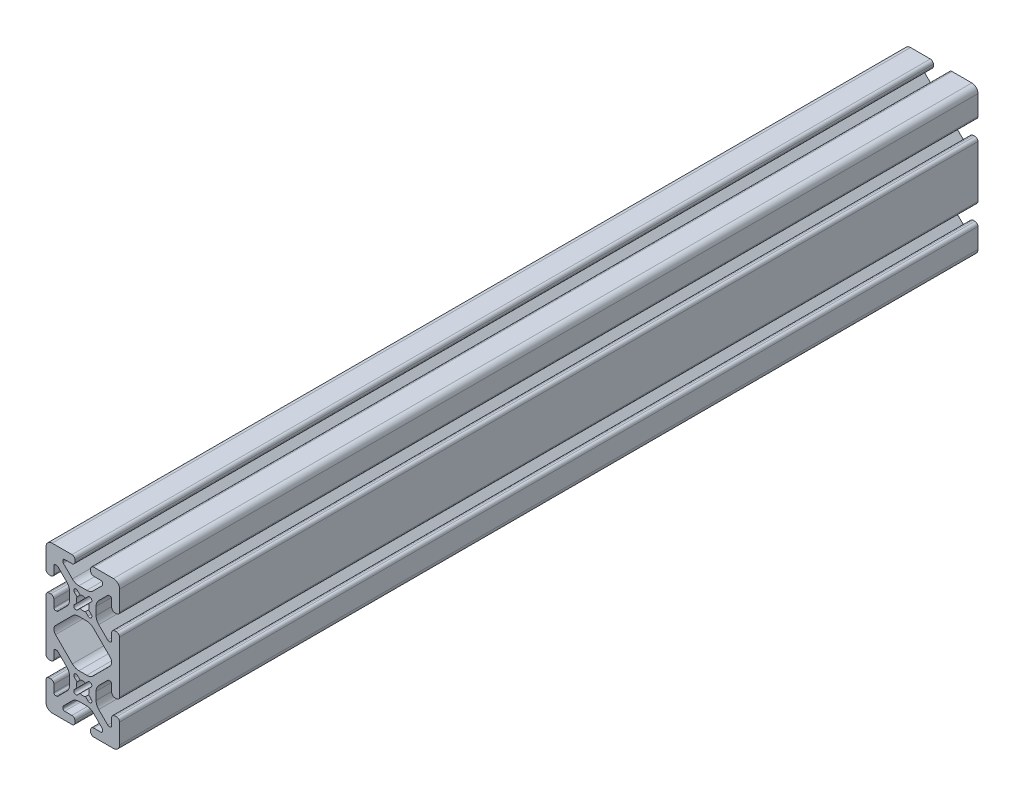
SolidWorks part; units mm, degrees
material "6063-T6"
ref_plane "Front Plane" through (0, 0, 0) normal (0, 0, 1) x (1, 0, 0)
ref_plane "Top Plane" through (0, 0, 0) normal (0, 1, 0) x (1, 0, 0)
ref_plane "Right Plane" through (0, 0, 0) normal (1, 0, 0) x (0, 0, -1)
ref_plane "Plane1" through (0, 0, -25.4) normal (0, 0, -1) x (-1, 0, 0)
sketch "Sketch1" plane through (0, 0, -25.4) normal (0, 0, -1) x (-1, 0, 0)
  line L0 (5.3872, 29.8392) -> (14.1109, 21.1155)
  line L1 (14.1109, 16.9845) -> (5.3872, 8.2608)
  line L2 (2.0285, 6.8697) -> (-2.0285, 6.8697)
  line L3 (-5.3872, 8.2608) -> (-14.1109, 16.9845)
  line L4 (-14.1109, 21.1155) -> (-5.3872, 29.8392)
  line L5 (-2.0285, 31.2303) -> (2.0285, 31.2303)
  line L6 (1.4014, 3.0179) -> (2.7269, 4.3433)
  line L7 (4.3433, 2.7269) -> (3.0179, 1.4014)
  line L8 (3.0179, -1.4014) -> (4.3433, -2.7269)
  line L9 (2.7269, -4.3433) -> (1.4014, -3.0179)
  line L10 (-1.4014, -3.0179) -> (-2.7269, -4.3433)
  line L11 (-4.3433, -2.7269) -> (-3.0179, -1.4014)
  line L12 (-3.0179, 1.4014) -> (-4.3433, 2.7269)
  line L13 (-2.7269, 4.3433) -> (-1.4014, 3.0179)
  line L14 (3.0179, 36.6986) -> (4.3433, 35.3731)
  line L15 (2.7269, 33.7567) -> (1.4014, 35.0821)
  line L16 (-1.4014, 35.0821) -> (-2.7269, 33.7567)
  line L17 (-4.3433, 35.3731) -> (-3.0179, 36.6986)
  line L18 (-3.0179, 39.5014) -> (-4.3433, 40.8269)
  line L19 (-2.7269, 42.4433) -> (-1.4014, 41.1179)
  line L20 (1.4014, 41.1179) -> (2.7269, 42.4433)
  line L21 (4.3433, 40.8269) -> (3.0179, 39.5014)
  line L22 (17.4752, 34.036) -> (16.5608, 34.036)
  line L23 (14.986, 32.4612) -> (14.986, 28.702)
  line L24 (14.097, 27.813) -> (13.5289, 27.813)
  line L25 (12.9003, 28.0734) -> (8.2608, 32.7128)
  line L26 (6.8697, 36.0715) -> (6.8697, 40.1285)
  line L27 (8.2608, 43.4872) -> (12.9003, 48.1266)
  line L28 (13.5289, 48.387) -> (14.097, 48.387)
  line L29 (14.986, 47.498) -> (14.986, 43.7388)
  line L30 (16.5608, 42.164) -> (17.4752, 42.164)
  line L31 (19.05, 43.7388) -> (19.05, 53.975)
  line L32 (15.875, 57.15) -> (5.6388, 57.15)
  line L33 (4.064, 55.5752) -> (4.064, 54.6608)
  line L34 (5.6388, 53.086) -> (9.398, 53.086)
  line L35 (10.287, 52.197) -> (10.287, 51.6289)
  line L36 (10.0266, 51.0003) -> (5.3872, 46.3608)
  line L37 (2.0285, 44.9697) -> (-2.0285, 44.9697)
  line L38 (-5.3872, 46.3608) -> (-10.0266, 51.0003)
  line L39 (-10.287, 51.6289) -> (-10.287, 52.197)
  line L40 (-9.398, 53.086) -> (-5.6388, 53.086)
  line L41 (-4.064, 54.6608) -> (-4.064, 55.5752)
  line L42 (-5.6388, 57.15) -> (-15.875, 57.15)
  line L43 (-19.05, 53.975) -> (-19.05, 43.7388)
  line L44 (-17.4752, 42.164) -> (-16.5608, 42.164)
  line L45 (-14.986, 43.7388) -> (-14.986, 47.498)
  line L46 (-14.097, 48.387) -> (-13.5289, 48.387)
  line L47 (-12.9003, 48.1266) -> (-8.2608, 43.4872)
  line L48 (-6.8697, 40.1285) -> (-6.8697, 36.0715)
  line L49 (-8.2608, 32.7128) -> (-12.9003, 28.0734)
  line L50 (-13.5289, 27.813) -> (-14.097, 27.813)
  line L51 (-14.986, 28.702) -> (-14.986, 32.4612)
  line L52 (-16.5608, 34.036) -> (-17.4752, 34.036)
  line L53 (-19.05, 32.4612) -> (-19.05, 5.6388)
  line L54 (-17.4752, 4.064) -> (-16.5608, 4.064)
  line L55 (-14.986, 5.6388) -> (-14.986, 9.398)
  line L56 (-14.097, 10.287) -> (-13.5289, 10.287)
  line L57 (-12.9003, 10.0266) -> (-8.2608, 5.3872)
  line L58 (-6.8697, 2.0285) -> (-6.8697, -2.0285)
  line L59 (-8.2608, -5.3872) -> (-12.9003, -10.0266)
  line L60 (-13.5289, -10.287) -> (-14.097, -10.287)
  line L61 (-14.986, -9.398) -> (-14.986, -5.6388)
  line L62 (-16.5608, -4.064) -> (-17.4752, -4.064)
  line L63 (-19.05, -5.6388) -> (-19.05, -15.875)
  line L64 (-15.875, -19.05) -> (-5.6388, -19.05)
  line L65 (-4.064, -17.4752) -> (-4.064, -16.5608)
  line L66 (-5.6388, -14.986) -> (-9.398, -14.986)
  line L67 (-10.287, -14.097) -> (-10.287, -13.5289)
  line L68 (-10.0266, -12.9003) -> (-5.3872, -8.2608)
  line L69 (-2.0285, -6.8697) -> (2.0285, -6.8697)
  line L70 (5.3872, -8.2608) -> (10.0266, -12.9003)
  line L71 (10.287, -13.5289) -> (10.287, -14.097)
  line L72 (9.398, -14.986) -> (5.6388, -14.986)
  line L73 (4.064, -16.5608) -> (4.064, -17.4752)
  line L74 (5.6388, -19.05) -> (15.875, -19.05)
  line L75 (19.05, -15.875) -> (19.05, -5.6388)
  line L76 (17.4752, -4.064) -> (16.5608, -4.064)
  line L77 (14.986, -5.6388) -> (14.986, -9.398)
  line L78 (14.097, -10.287) -> (13.5289, -10.287)
  line L79 (12.9003, -10.0266) -> (8.2608, -5.3872)
  line L80 (6.8697, -2.0285) -> (6.8697, 2.0285)
  line L81 (8.2608, 5.3872) -> (12.9003, 10.0266)
  line L82 (13.5289, 10.287) -> (14.097, 10.287)
  line L83 (14.986, 9.398) -> (14.986, 5.6388)
  line L84 (16.5608, 4.064) -> (17.4752, 4.064)
  line L85 (19.05, 5.6388) -> (19.05, 32.4612)
  arc A0 (14.1109, 21.1155) -> (14.1109, 16.9845) centre (12.0454, 19.05) cw
  arc A1 (5.3872, 8.2608) -> (2.0285, 6.8697) centre (2.0285, 11.6195) cw
  arc A2 (-2.0285, 6.8697) -> (-5.3872, 8.2608) centre (-2.0285, 11.6195) cw
  arc A3 (-14.1109, 16.9845) -> (-14.1109, 21.1155) centre (-12.0454, 19.05) cw
  arc A4 (-5.3872, 29.8392) -> (-2.0285, 31.2303) centre (-2.0285, 26.4805) cw
  arc A5 (2.0285, 31.2303) -> (5.3872, 29.8392) centre (2.0285, 26.4805) cw
  arc A6 (2.7269, 4.3433) -> (4.3433, 2.7269) centre (3.5351, 3.5351) cw
  arc A7 (3.0179, 1.4014) -> (3.0179, -1.4014) centre (0, 0) cw
  arc A8 (4.3433, -2.7269) -> (2.7269, -4.3433) centre (3.5351, -3.5351) cw
  arc A9 (1.4014, -3.0179) -> (-1.4014, -3.0179) centre (0, 0) cw
  arc A10 (-2.7269, -4.3433) -> (-4.3433, -2.7269) centre (-3.5351, -3.5351) cw
  arc A11 (-3.0179, -1.4014) -> (-3.0179, 1.4014) centre (0, 0) cw
  arc A12 (-4.3433, 2.7269) -> (-2.7269, 4.3433) centre (-3.5351, 3.5351) cw
  arc A13 (-1.4014, 3.0179) -> (1.4014, 3.0179) centre (0, 0) cw
  arc A14 (4.3433, 35.3731) -> (2.7269, 33.7567) centre (3.5351, 34.5649) cw
  arc A15 (1.4014, 35.0821) -> (-1.4014, 35.0821) centre (0, 38.1) cw
  arc A16 (-2.7269, 33.7567) -> (-4.3433, 35.3731) centre (-3.5351, 34.5649) cw
  arc A17 (-3.0179, 36.6986) -> (-3.0179, 39.5014) centre (0, 38.1) cw
  arc A18 (-4.3433, 40.8269) -> (-2.7269, 42.4433) centre (-3.5351, 41.6351) cw
  arc A19 (-1.4014, 41.1179) -> (1.4014, 41.1179) centre (0, 38.1) cw
  arc A20 (2.7269, 42.4433) -> (4.3433, 40.8269) centre (3.5351, 41.6351) cw
  arc A21 (3.0179, 39.5014) -> (3.0179, 36.6986) centre (0, 38.1) cw
  arc A22 (19.05, 32.4612) -> (17.4752, 34.036) centre (17.4752, 32.4612) ccw
  arc A23 (16.5608, 34.036) -> (14.986, 32.4612) centre (16.5608, 32.4612) ccw
  arc A24 (14.986, 28.702) -> (14.097, 27.813) centre (14.097, 28.702) cw
  arc A25 (13.5289, 27.813) -> (12.9003, 28.0734) centre (13.5289, 28.702) cw
  arc A26 (8.2608, 32.7128) -> (6.8697, 36.0715) centre (11.6195, 36.0715) cw
  arc A27 (6.8697, 40.1285) -> (8.2608, 43.4872) centre (11.6195, 40.1285) cw
  arc A28 (12.9003, 48.1266) -> (13.5289, 48.387) centre (13.5289, 47.498) cw
  arc A29 (14.097, 48.387) -> (14.986, 47.498) centre (14.097, 47.498) cw
  arc A30 (14.986, 43.7388) -> (16.5608, 42.164) centre (16.5608, 43.7388) ccw
  arc A31 (17.4752, 42.164) -> (19.05, 43.7388) centre (17.4752, 43.7388) ccw
  arc A32 (19.05, 53.975) -> (15.875, 57.15) centre (15.875, 53.975) ccw
  arc A33 (5.6388, 57.15) -> (4.064, 55.5752) centre (5.6388, 55.5752) ccw
  arc A34 (4.064, 54.6608) -> (5.6388, 53.086) centre (5.6388, 54.6608) ccw
  arc A35 (9.398, 53.086) -> (10.287, 52.197) centre (9.398, 52.197) cw
  arc A36 (10.287, 51.6289) -> (10.0266, 51.0003) centre (9.398, 51.6289) cw
  arc A37 (5.3872, 46.3608) -> (2.0285, 44.9697) centre (2.0285, 49.7195) cw
  arc A38 (-2.0285, 44.9697) -> (-5.3872, 46.3608) centre (-2.0285, 49.7195) cw
  arc A39 (-10.0266, 51.0003) -> (-10.287, 51.6289) centre (-9.398, 51.6289) cw
  arc A40 (-10.287, 52.197) -> (-9.398, 53.086) centre (-9.398, 52.197) cw
  arc A41 (-5.6388, 53.086) -> (-4.064, 54.6608) centre (-5.6388, 54.6608) ccw
  arc A42 (-4.064, 55.5752) -> (-5.6388, 57.15) centre (-5.6388, 55.5752) ccw
  arc A43 (-15.875, 57.15) -> (-19.05, 53.975) centre (-15.875, 53.975) ccw
  arc A44 (-19.05, 43.7388) -> (-17.4752, 42.164) centre (-17.4752, 43.7388) ccw
  arc A45 (-16.5608, 42.164) -> (-14.986, 43.7388) centre (-16.5608, 43.7388) ccw
  arc A46 (-14.986, 47.498) -> (-14.097, 48.387) centre (-14.097, 47.498) cw
  arc A47 (-13.5289, 48.387) -> (-12.9003, 48.1266) centre (-13.5289, 47.498) cw
  arc A48 (-8.2608, 43.4872) -> (-6.8697, 40.1285) centre (-11.6195, 40.1285) cw
  arc A49 (-6.8697, 36.0715) -> (-8.2608, 32.7128) centre (-11.6195, 36.0715) cw
  arc A50 (-12.9003, 28.0734) -> (-13.5289, 27.813) centre (-13.5289, 28.702) cw
  arc A51 (-14.097, 27.813) -> (-14.986, 28.702) centre (-14.097, 28.702) cw
  arc A52 (-14.986, 32.4612) -> (-16.5608, 34.036) centre (-16.5608, 32.4612) ccw
  arc A53 (-17.4752, 34.036) -> (-19.05, 32.4612) centre (-17.4752, 32.4612) ccw
  arc A54 (-19.05, 5.6388) -> (-17.4752, 4.064) centre (-17.4752, 5.6388) ccw
  arc A55 (-16.5608, 4.064) -> (-14.986, 5.6388) centre (-16.5608, 5.6388) ccw
  arc A56 (-14.986, 9.398) -> (-14.097, 10.287) centre (-14.097, 9.398) cw
  arc A57 (-13.5289, 10.287) -> (-12.9003, 10.0266) centre (-13.5289, 9.398) cw
  arc A58 (-8.2608, 5.3872) -> (-6.8697, 2.0285) centre (-11.6195, 2.0285) cw
  arc A59 (-6.8697, -2.0285) -> (-8.2608, -5.3872) centre (-11.6195, -2.0285) cw
  arc A60 (-12.9003, -10.0266) -> (-13.5289, -10.287) centre (-13.5289, -9.398) cw
  arc A61 (-14.097, -10.287) -> (-14.986, -9.398) centre (-14.097, -9.398) cw
  arc A62 (-14.986, -5.6388) -> (-16.5608, -4.064) centre (-16.5608, -5.6388) ccw
  arc A63 (-17.4752, -4.064) -> (-19.05, -5.6388) centre (-17.4752, -5.6388) ccw
  arc A64 (-19.05, -15.875) -> (-15.875, -19.05) centre (-15.875, -15.875) ccw
  arc A65 (-5.6388, -19.05) -> (-4.064, -17.4752) centre (-5.6388, -17.4752) ccw
  arc A66 (-4.064, -16.5608) -> (-5.6388, -14.986) centre (-5.6388, -16.5608) ccw
  arc A67 (-9.398, -14.986) -> (-10.287, -14.097) centre (-9.398, -14.097) cw
  arc A68 (-10.287, -13.5289) -> (-10.0266, -12.9003) centre (-9.398, -13.5289) cw
  arc A69 (-5.3872, -8.2608) -> (-2.0285, -6.8697) centre (-2.0285, -11.6195) cw
  arc A70 (2.0285, -6.8697) -> (5.3872, -8.2608) centre (2.0285, -11.6195) cw
  arc A71 (10.0266, -12.9003) -> (10.287, -13.5289) centre (9.398, -13.5289) cw
  arc A72 (10.287, -14.097) -> (9.398, -14.986) centre (9.398, -14.097) cw
  arc A73 (5.6388, -14.986) -> (4.064, -16.5608) centre (5.6388, -16.5608) ccw
  arc A74 (4.064, -17.4752) -> (5.6388, -19.05) centre (5.6388, -17.4752) ccw
  arc A75 (15.875, -19.05) -> (19.05, -15.875) centre (15.875, -15.875) ccw
  arc A76 (19.05, -5.6388) -> (17.4752, -4.064) centre (17.4752, -5.6388) ccw
  arc A77 (16.5608, -4.064) -> (14.986, -5.6388) centre (16.5608, -5.6388) ccw
  arc A78 (14.986, -9.398) -> (14.097, -10.287) centre (14.097, -9.398) cw
  arc A79 (13.5289, -10.287) -> (12.9003, -10.0266) centre (13.5289, -9.398) cw
  arc A80 (8.2608, -5.3872) -> (6.8697, -2.0285) centre (11.6195, -2.0285) cw
  arc A81 (6.8697, 2.0285) -> (8.2608, 5.3872) centre (11.6195, 2.0285) cw
  arc A82 (12.9003, 10.0266) -> (13.5289, 10.287) centre (13.5289, 9.398) cw
  arc A83 (14.097, 10.287) -> (14.986, 9.398) centre (14.097, 9.398) cw
  arc A84 (14.986, 5.6388) -> (16.5608, 4.064) centre (16.5608, 5.6388) ccw
  arc A85 (17.4752, 4.064) -> (19.05, 5.6388) centre (17.4752, 5.6388) ccw
extrude "Boss-Extrude1" add sketch "Sketch1" against normal blind 444.5
equation "\"D1@Boss-Extrude1\"=(38-3)/2in"
